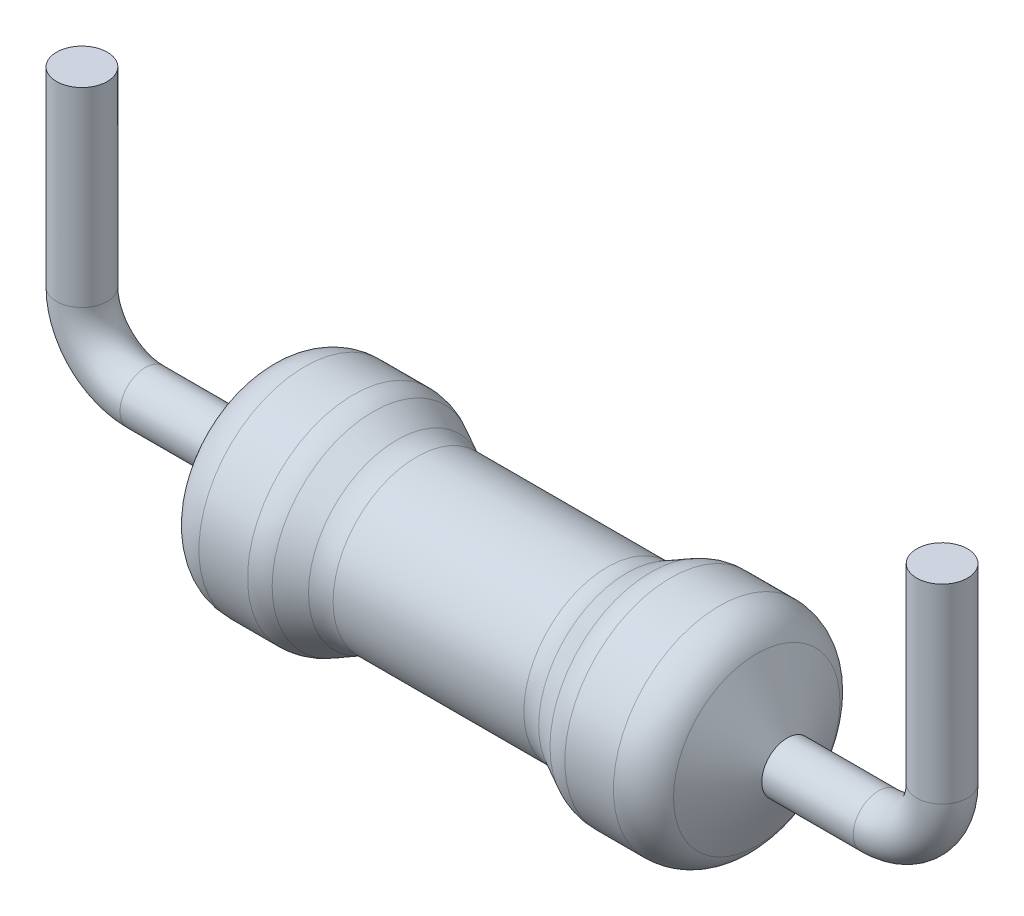
SolidWorks part; units mm, degrees
ref_plane "Front Plane" through (0, 0, 0) normal (0, 0, 1) x (1, 0, 0)
ref_plane "Top Plane" through (0, 0, 0) normal (0, 1, 0) x (1, 0, 0)
ref_plane "Right Plane" through (0, 0, 0) normal (1, 0, 0) x (0, 0, -1)
sketch "Sketch1" plane through (0, 0, 0) normal (0, 0, 1) x (1, 0, 0)
  line L0 (0, 0) -> (3.25, 0)
  line L1 (3.25, 0) -> (3.25, 0.3)
  line L2 (3.25, 0.3) -> (2.75, 1.25)
  line L3 (2.75, 1.25) -> (1.75, 1.25)
  line L4 (1.75, 1.25) -> (1.25, 0.9868)
  line L5 (1.25, 0.9868) -> (-1.25, 0.9868)
  line L6 (-1.25, 0.9868) -> (-1.75, 1.25)
  line L7 (-1.75, 1.25) -> (-2.75, 1.25)
  line L8 (-2.75, 1.25) -> (-3.25, 0.3)
  line L9 (-3.25, 0.3) -> (-3.25, 0)
  line L10 (-3.25, 0) -> (0, 0)
  point P2 (2.25, 1.25)
  dimension "D1" = 0.3
  dimension "D2" = 0.3
  dimension "D3" = 3.25
  dimension "D4" = 3.25
  dimension "D5" = 1.25
  dimension "D6" = 1.25
  dimension "D7" = 0.5
  dimension "D8" = 0.5
  dimension "D9" = 1
  dimension "D12" = 0.5
  dimension "D13" = 0.9868
revolve "Revolve1" add sketch "Sketch1" angle 360 about L0
fillet "Fillet1" radius 0.5 6 edges at (-2.75, 0, 1.25) (-1.75, 0, 1.25) (-1.25, 0, 0.9868) (1.25, 0, 0.9868) (1.75, 0, 1.25) (2.75, 0, 1.25)
sketch "Sketch4" plane through (3.25, 0, 0) normal (1, 0, 0) x (0, 0, -1)
  circle A0 centre (0, 0) radius 0.3
  circle A1 centre (0, 0) radius 0.3 construction
sketch "Sketch6" plane through (0, 0, 0) normal (0, 0, 1) x (1, 0, 0)
  line L0 (3.25, 0) -> (4.33, 0)
  line L1 (5.08, 0.75) -> (5.08, 3)
  line L2 (3.25, 0) -> (-4.33, 0)
  line L3 (-5.08, 0.75) -> (-5.08, 3)
  arc A0 (-4.33, 0) -> (-5.08, 0.75) centre (-4.33, 0.75) cw
  arc A1 (4.33, 0) -> (5.08, 0.75) centre (4.33, 0.75) ccw
  point P8 (-5.08, 0)
  point P11 (5.08, 0)
  dimension "D5" = 0.75
  dimension "D1" = 1.83
  dimension "D2" = 3
  dimension "D3" = 8.33
  dimension "D4" = 3
sweep "Sweep1" add profiles "Sketch4" path "Sketch6"
